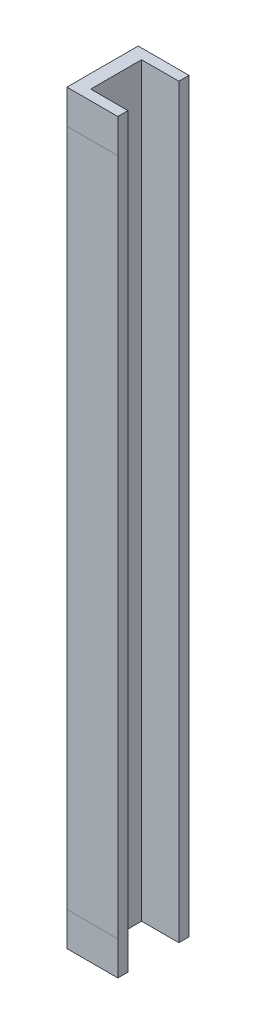
SolidWorks part; units mm, degrees
ref_plane "Płaszczyzna przednia" through (0, 0, 0) normal (0, 0, 1) x (1, 0, 0)
ref_plane "Płaszczyzna górna" through (0, 0, 0) normal (0, 1, 0) x (1, 0, 0)
ref_plane "Płaszczyzna prawa" through (0, 0, 0) normal (1, 0, 0) x (0, 0, -1)
sketch "Szkic1" plane through (0, 0, 0) normal (0, 1, 0) x (1, 0, 0)
  line L0 (0, 0) -> (150, 0)
  line L1 (150, 0) -> (150, 30)
  line L2 (150, 30) -> (40, 30)
  line L3 (40, 30) -> (40, 180)
  line L4 (40, 180) -> (150, 180)
  line L5 (150, 180) -> (150, 210)
  line L6 (150, 210) -> (0, 210)
  line L7 (0, 210) -> (0, 0)
  dimension "D1" = 150
  dimension "D2" = 110
  dimension "D3" = 210
  dimension "D4" = 150
extrude "Dodanie-wyciągnięcie1" add sketch "Szkic1" along normal blind 2200
sketch "Szkic2" plane through (0, 0, 0) normal (0, 0, 1) x (1, 0, 0)
  line L0 (0, 2100) -> (150, 2100)
  line L1 (0, 2200) -> (0, 0) construction
  line L2 (150, 2200) -> (150, 0) construction
  line L3 (0, 100) -> (150, 100)
  line L4 (0, 2200) -> (150, 2200) construction
  line L5 (0, 0) -> (150, 0) construction
  dimension "D1" = 100
  dimension "D2" = 100
split line "Linia podziałowa1"
